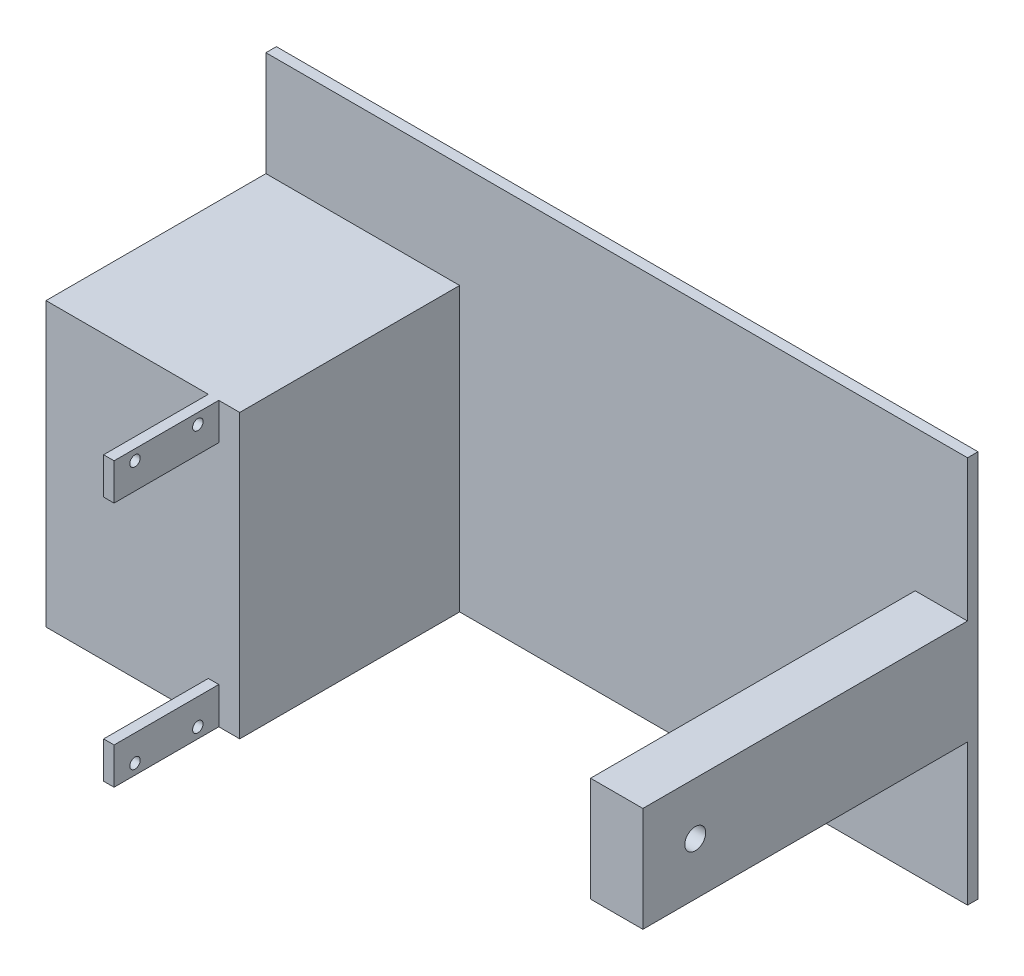
SolidWorks part; units mm, degrees
ref_plane "Front Plane" through (0, 0, 0) normal (0, 0, 1) x (1, 0, 0)
ref_plane "Top Plane" through (0, 0, 0) normal (0, 1, 0) x (1, 0, 0)
ref_plane "Right Plane" through (0, 0, 0) normal (1, 0, 0) x (0, 0, -1)
sketch "Sketch1" plane through (0, 0, 0) normal (0, 0, 1) x (1, 0, 0)
  line L1 (-18.5, -27) -> (18.5, -27)
  line L2 (-18.5, -27) -> (-18.5, 27)
  line L3 (-18.5, 27) -> (18.5, 27)
  line L4 (18.5, -27) -> (18.5, 27)
  line L5 (-18.5, -27) -> (18.5, 27) construction
  line L6 (-18.5, 27) -> (18.5, -27) construction
  point P0 (0, 0)
  dimension "D1" = 54
  dimension "D2" = 37
extrude "Boss-Extrude1" add sketch "Sketch1" along normal blind 2
sketch "Sketch2" plane through (0, 0, 2) normal (0, 0, 1) x (1, 0, 0)
  line L0 (-18.5, -27) -> (18.5, -27) construction
  line L1 (18.5, 27) -> (-18.5, 27) construction
  line L2 (-18.5, 27) -> (-18.5, -27) construction
  line L3 (12.5, -27) -> (14.5, -27)
  line L4 (12.5, -27) -> (12.5, -20)
  line L5 (12.5, -20) -> (14.5, -20)
  line L6 (14.5, -27) -> (14.5, -20)
  line L8 (12.5, 27) -> (14.5, 27)
  line L9 (12.5, 27) -> (12.5, 20)
  line L10 (12.5, 20) -> (14.5, 20)
  line L11 (14.5, 27) -> (14.5, 20)
  point P0 (12.5, -27)
  point P1 (14.5, -27)
  point P4 (12.5, 27)
  point P7 (14.5, 27)
  dimension "D1" = 31
  dimension "D2" = 2
  dimension "D3" = 7
  dimension "D4" = 7
extrude "Boss-Extrude2" add sketch "Sketch2" along normal blind 20
sketch "Sketch3" plane through (12.5, 0, 0) normal (-1, 0, 0) x (0, 0, 1)
  line L0 (2, 27) -> (2, -27) construction
  line L3 (22, -27) -> (2, -27) construction
  line L4 (22, -20) -> (22, -27) construction
  line L5 (22, 27) -> (2, 27) construction
  circle A0 centre (6, -25) radius 1
  circle A1 centre (18, -25) radius 1
  circle A2 centre (6, 25) radius 1
  circle A3 centre (18, 25) radius 1
  point P0 (6, -25)
  point P5 (18, -25)
  point P12 (6, 25)
  point P13 (18, 25)
  dimension "D3" = 2
  dimension "D5" = 2
  dimension "D7" = 2
  dimension "D8" = 2
  dimension "D1" = 4
  dimension "D2" = 2
  dimension "D4" = 4
  dimension "D6" = 2
  dimension "D9" = 2
  dimension "D10" = 2
extrude "Cut-Extrude1" cut sketch "Sketch3" against normal up to next
sketch "Sketch11" plane through (0, 0, 0) normal (0, 0, -1) x (-1, 0, 0)
  line L1 (-18.5, -27) -> (18.5, -27)
  line L2 (-18.5, -27) -> (-18.5, 27)
  line L3 (-18.5, 27) -> (18.5, 27)
  line L4 (18.5, -27) -> (18.5, 27)
  line L5 (-18.5, -27) -> (18.5, 27) construction
  line L6 (-18.5, 27) -> (18.5, -27) construction
  line L7 (-16.5, -25) -> (16.5, -25)
  line L8 (-16.5, -25) -> (-16.5, 25)
  line L9 (-16.5, 25) -> (16.5, 25)
  line L10 (16.5, -25) -> (16.5, 25)
  line L11 (-16.5, -25) -> (16.5, 25) construction
  line L12 (-16.5, 25) -> (16.5, -25) construction
  point P0 (0, 0)
  point P7 (0, 0)
  dimension "D1" = 33
  dimension "D2" = 50
extrude "Boss-Extrude5" add sketch "Sketch11" along normal blind 40
sketch "Sketch12" plane through (0, 0, -40) normal (0, 0, -1) x (-1, 0, 0)
  line L0 (18.5, -27) -> (18.5, 27) construction
  line L1 (-18.5, -27) -> (18.5, -27) construction
  line L3 (18.5, -27) -> (-115.5, -27)
  line L4 (18.5, -27) -> (18.5, 47)
  line L5 (18.5, 47) -> (-115.5, 47)
  line L6 (-115.5, -27) -> (-115.5, 47)
  point P0 (18.5, 10)
  point P5 (18.5, 10)
  point P6 (18.5, 47)
  dimension "D1" = 37
  dimension "D2" = 37
  dimension "D3" = 134
extrude "Boss-Extrude6" add sketch "Sketch12" along normal blind 2
sketch "Sketch13" plane through (0, 0, -40) normal (0, 0, 1) x (1, 0, 0)
  line L0 (115.5, 47) -> (115.5, -27) construction
  line L1 (115.5, 20) -> (115.5, 0)
  line L2 (115.5, 0) -> (105.5, 0)
  line L4 (115.5, 20) -> (105.5, 20)
  line L5 (105.5, 0) -> (105.5, 20)
  line L6 (115.5, 10) -> (105.5, 20) construction
  line L7 (115.5, 10) -> (105.5, 0) construction
  point P0 (115.5, 10)
  point P1 (115.5, 10)
  dimension "D1" = 10
extrude "Boss-Extrude7" add sketch "Sketch13" along normal blind 62
sketch "Sketch16" plane through (115.5, 0, 0) normal (1, 0, 0) x (0, 0, -1)
  line L1 (40, 0) -> (40, -27) construction
  circle A0 centre (-12, 10) radius 2
  point P0 (-12, 10)
  dimension "D2" = 4
  dimension "D1" = 52
extrude "Cut-Extrude2" cut sketch "Sketch16" against normal up to next
